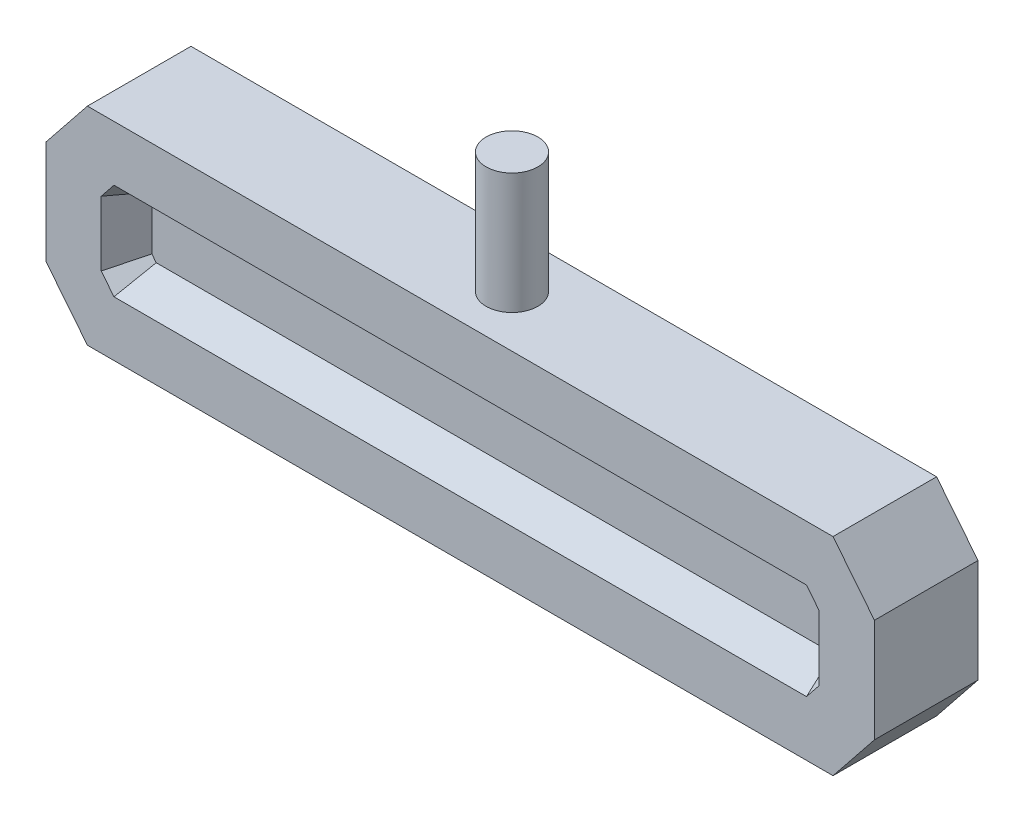
SolidWorks part; units mm, degrees
ref_plane "Front Plane" through (0, 0, 0) normal (0, 0, 1) x (1, 0, 0)
ref_plane "Top Plane" through (0, 0, 0) normal (0, 1, 0) x (1, 0, 0)
ref_plane "Right Plane" through (0, 0, 0) normal (1, 0, 0) x (0, 0, -1)
sketch "Sketch2" plane through (0, 0, 0) normal (0, 0, 1) x (1, 0, 0)
  line L0 (-160.8106, 0) -> (160.8106, 0) construction
  line L2 (-137.16, 76.2) -> (137.16, 76.2)
  line L3 (137.16, 76.2) -> (152.4, 57.15)
  line L4 (152.4, 57.15) -> (152.4, 19.05)
  line L5 (152.4, 19.05) -> (137.16, 0)
  line L6 (137.16, 0) -> (-137.16, 0)
  line L7 (0, 0) -> (0, 119.5747) construction
  line L8 (-152.4, 19.05) -> (-137.16, 0)
  line L9 (-152.4, 57.15) -> (-152.4, 19.05)
  line L10 (-137.16, 76.2) -> (-152.4, 57.15)
  point P14 (0, 76.2)
  dimension "D1" = 76.2
  dimension "D2" = 152.4
  dimension "D3" = 38.1
  dimension "D4" = 137.16
  dimension "D5" = 19.05
extrude "Boss-Extrude1" add sketch "Sketch2" along normal mid plane 38.1
sketch3d "3DSketch1"
  line L0 (127.3937, 20.32, 19.05) -> (132.08, 26.1779, 19.05)
  line L1 (132.08, 26.1779, 19.05) -> (132.08, 50.0221, 19.05)
  line L2 (132.08, 50.0221, 19.05) -> (127.3937, 55.88, 19.05)
  line L3 (127.3937, 55.88, 19.05) -> (-127.3937, 55.88, 19.05)
  line L4 (-127.3937, 55.88, 19.05) -> (-132.08, 50.0221, 19.05)
  line L5 (-132.08, 50.0221, 19.05) -> (-132.08, 26.1779, 19.05)
  line L6 (-132.08, 26.1779, 19.05) -> (-127.3937, 20.32, 19.05)
  line L7 (-127.3937, 20.32, 19.05) -> (127.3937, 20.32, 19.05)
  line L8 (127.3937, 20.32, 19.05) -> (132.08, 26.1779, 19.05)
  line L9 (132.08, 26.1779, 19.05) -> (132.08, 50.0221, 19.05)
  line L10 (132.08, 50.0221, 19.05) -> (127.3937, 55.88, 19.05)
  line L11 (127.3937, 55.88, 19.05) -> (-127.3937, 55.88, 19.05)
  line L12 (-127.3937, 55.88, 19.05) -> (-132.08, 50.0221, 19.05)
  line L13 (-132.08, 50.0221, 19.05) -> (-132.08, 26.1779, 19.05)
  line L14 (-132.08, 26.1779, 19.05) -> (-127.3937, 20.32, 19.05)
  line L15 (-127.3937, 20.32, 19.05) -> (127.3937, 20.32, 19.05)
  dimension "D1" = 20.32
extrude "Cut-Extrude1" cut sketch "3DSketch1" along direction (0, 0, -1) on the side of the normal blind 12.7 draft 25
sketch "Sketch9" plane through (0, 76.2, 0) normal (0, 1, 0) x (1, 0, 0)
  line L0 (137.16, -19.05) -> (137.16, 19.05) construction
  line L1 (137.16, -19.05) -> (-137.16, -19.05) construction
  line L2 (137.16, 19.05) -> (-137.16, 19.05) construction
  line L3 (-137.16, -19.05) -> (-137.16, 19.05) construction
  line L4 (137.16, -19.05) -> (137.16, 19.05)
  line L5 (137.16, -19.05) -> (-137.16, -19.05)
  line L6 (137.16, 19.05) -> (-137.16, 19.05)
  line L7 (-137.16, -19.05) -> (-137.16, 19.05)
  circle A0 centre (0, 0) radius 9.525
  point P7 (0, 0)
  dimension "D1" = 19.05
extrude "Boss-Extrude3" add sketch "Sketch9" along normal blind 44.45 contours A0
